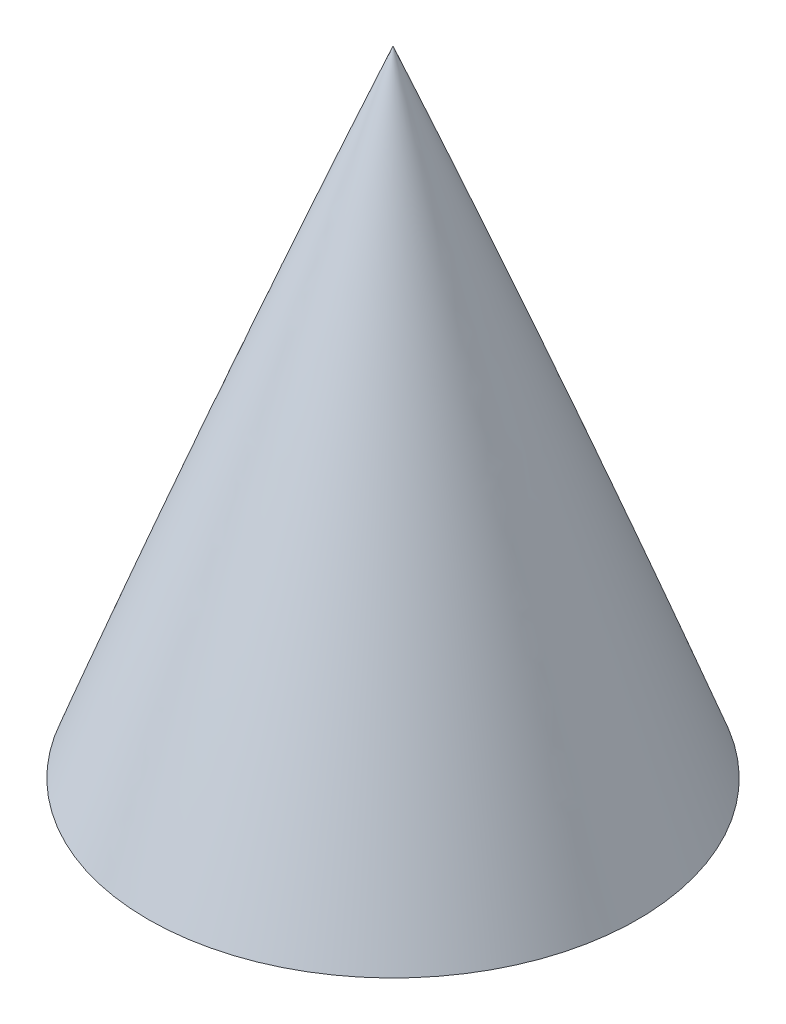
SolidWorks part; units mm, degrees
other "Markup1"
sketch "Sketch4" plane through (78.16, -154.2442, 78.16) normal (0.9651, -0.1718, 0.1975) x (-0.1686, -0.9851, -0.0334)
material "1060 Alloy"
ref_plane "Front Plane" through (0, 0, 0) normal (0, 0, 1) x (1, 0, 0)
ref_plane "Top Plane" through (0, 0, 0) normal (0, 1, 0) x (1, 0, 0)
ref_plane "Right Plane" through (0, 0, 0) normal (1, 0, 0) x (0, 0, -1)
sketch "Sketch1" plane through (0, 0, 0) normal (0, 0, 1) x (1, 0, 0)
  line L3 (0, 0) -> (0, 398.8705) construction
  line L6 (0, 400) -> (0, 401.8534)
  line L8 (78.2, 0) -> (76.2, 0)
  line L9 (0, 400) -> (0, 396.4892)
  line L10 (76.2, 0) -> (-993.4203, 0) construction
  line L11 (0, 411.0234) -> (0, 614.1078) construction
  arc A0 (76.2, 0) -> (0, 396.4892) centre (-993.4203, 0) ccw
  arc A1 (78.2, 0) -> (0, 401.8534) centre (-993.4203, 0) ccw
  circle A2 centre (-993.4203, 0) radius 1069.6203 construction
  circle A3 centre (-993.4203, 0) radius 1071.6203 construction
  point P7 (0, 401.3589)
  point P11 (0, 400)
  point P12 (0, 0)
  point P19 (0, 0)
  dimension "D1" = 400
  dimension "D2" = 3.5108
  dimension "D3" = 2
  dimension "D4" = 76.2
revolve "Revolve3" add sketch "Sketch1" angle 360 about L6
sketch "Sketch2" plane through (0, 0, 0) normal (0, 1, 0) x (1, 0, 0)
  circle A3 centre (0, 0) radius 76.2 construction
  circle A4 centre (0, 0) radius 76.2
  circle A5 centre (0, 0) radius 74.2
  dimension "D1" = 2
extrude "Boss-Extrude1" add sketch "Sketch2" against normal blind 152.4 and the other way blind 10
ref_plane "Plane2" through (0, 400, 0) normal (0, -1, 0) x (-1, 0, 0)
ref_plane "Plane4" through (0, 370, 0) normal (0, -1, 0) x (-1, 0, 0)
sketch "Sketch6" plane through (0, 370, 0) normal (0, -1, 0) x (-1, 0, 0)
  circle A0 centre (0, 0) radius 147.184
extrude "Cut-Extrude1" cut sketch "Sketch6" along normal blind 1000 contours A0
